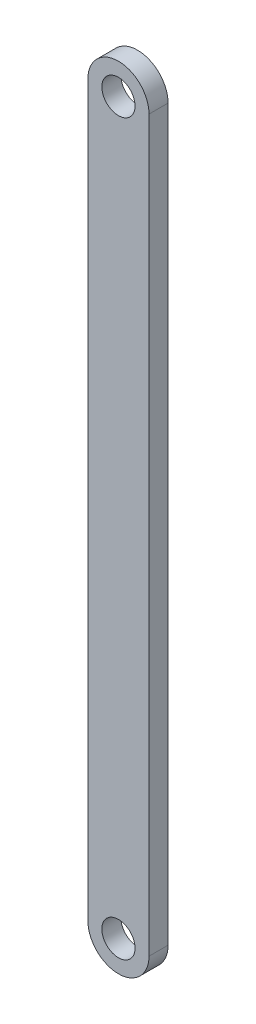
SolidWorks part; units mm, degrees
ref_plane "Front Plane" through (0, 0, 0) normal (0, 0, 1) x (1, 0, 0)
ref_plane "Top Plane" through (0, 0, 0) normal (0, 1, 0) x (1, 0, 0)
ref_plane "Right Plane" through (0, 0, 0) normal (1, 0, 0) x (0, 0, -1)
sketch "Sketch1" plane through (0, 0, 0) normal (0, 0, 1) x (1, 0, 0)
  line L0 (0, 0) -> (0, 191) construction
  line L1 (-8, 0) -> (-8, 191)
  line L2 (8, 0) -> (8, 191)
  arc A0 (-8, 0) -> (8, 0) centre (0, 0) ccw
  arc A1 (8, 191) -> (-8, 191) centre (0, 191) ccw
  circle A2 centre (0, 191) radius 4.35
  circle A3 centre (0, 0) radius 4.35
  point P3 (0, 95.5)
  dimension "D3" = 8.7
  dimension "D4" = 8.7
  dimension "D1" = 191
  dimension "D2" = 16
extrude "Boss-Extrude1" add sketch "Sketch1" along normal blind 5
